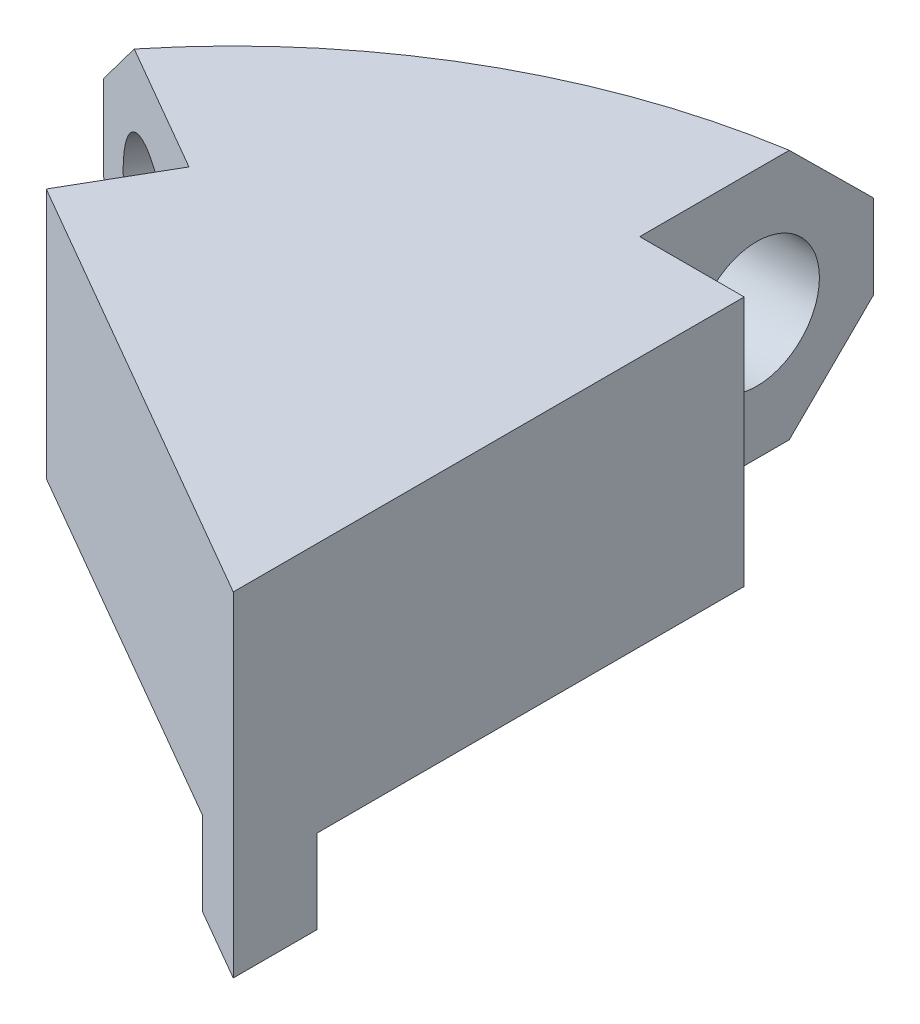
SolidWorks part; units mm, degrees
ref_plane "Alzado" through (0, 0, 0) normal (0, 0, 1) x (1, 0, 0)
ref_plane "Planta" through (0, 0, 0) normal (0, 1, 0) x (1, 0, 0)
ref_plane "Vista lateral" through (0, 0, 0) normal (1, 0, 0) x (0, 0, -1)
sketch "Croquis1" plane through (0, 0, 0) normal (0, 1, 0) x (1, 0, 0)
  line L6 (-136.7422, -20.0947) -> (-112.4935, -6.0947)
  line L7 (-112.4935, -6.0947) -> (-118.7435, 4.7306)
  line L8 (-118.7435, 4.7306) -> (-124.9935, 15.5559)
  line L9 (-124.9935, 15.5559) -> (-149.2422, 1.5559)
  line L10 (-149.2422, 69.033) -> (-124.9935, 55.033)
  line L11 (-124.9935, 55.033) -> (-118.7435, 65.8583)
  line L12 (-118.7435, 65.8583) -> (-112.4935, 76.6836)
  line L13 (-112.4935, 76.6836) -> (-136.7422, 90.6836)
  line L14 (-78.3054, 124.4222) -> (-78.3054, 96.4222)
  line L15 (-78.3054, 96.4222) -> (-65.8054, 96.4222)
  line L16 (-65.8054, 96.4222) -> (-53.3054, 96.4222)
  line L17 (-53.3054, 96.4222) -> (-53.3054, 124.4222)
  line L18 (5.1315, 90.6836) -> (-19.1172, 76.6836)
  line L19 (-19.1172, 76.6836) -> (-6.6172, 55.033)
  line L20 (-6.6172, 55.033) -> (17.6315, 69.033)
  line L21 (17.6315, 1.5559) -> (-6.6172, 15.5559)
  line L22 (-6.6172, 15.5559) -> (-12.8672, 4.7306)
  line L23 (-12.8672, 4.7306) -> (-19.1172, -6.0947)
  line L24 (-19.1172, -6.0947) -> (5.1315, -20.0947)
  line L25 (-78.3054, -53.8333) -> (-78.3054, -25.8333)
  line L26 (-78.3054, -25.8333) -> (-65.8054, -25.8333)
  line L27 (-65.8054, -25.8333) -> (-53.3054, -25.8333)
  line L28 (-53.3054, -25.8333) -> (-53.3054, -53.8333)
  arc A0 (-136.7422, -20.0947) -> (-78.3054, -53.8333) centre (-65.8054, 35.2945) ccw
  arc A1 (-53.3054, -53.8333) -> (5.1315, -20.0947) centre (-65.8054, 35.2945) ccw
  arc A2 (17.6315, 1.5559) -> (17.6315, 69.033) centre (-65.8054, 35.2945) ccw
  arc A3 (5.1315, 90.6836) -> (-53.3054, 124.4222) centre (-65.8054, 35.2945) ccw
  arc A4 (-149.2422, 69.033) -> (-149.2422, 1.5559) centre (-65.8054, 35.2945) ccw
  arc A5 (-78.3054, 124.4222) -> (-136.7422, 90.6836) centre (-65.8054, 35.2945) ccw
  dimension "D22" = 180
  dimension "D5" = 25
  dimension "D7" = 25
  dimension "D9" = 25
  dimension "D11" = 25
  dimension "D13" = 25
  dimension "D15" = 25
  dimension "D16" = 28
  dimension "D17" = 28
  dimension "D18" = 28
  dimension "D19" = 28
  dimension "D20" = 28
  dimension "D21" = 28
extrude "Saliente-Extruir1" add sketch "Croquis1" along normal mid plane 30
sketch "Croquis3" plane through (0, 15, 0) normal (0, 1, 0) x (1, 0, 0)
  line L0 (-65.8054, 96.4222) -> (-65.8054, 35.2945)
  line L1 (-53.3054, 96.4222) -> (-78.3054, 96.4222) construction
  line L3 (-118.7435, 65.8583) -> (-65.8054, 35.2945)
  line L4 (-112.4935, 76.6836) -> (-124.9935, 55.033) construction
  line L8 (-118.7435, 65.8583) -> (-112.4935, 76.6836)
  line L9 (-112.4935, 76.6836) -> (-136.7422, 90.6836)
  line L10 (-78.3054, 124.4222) -> (-78.3054, 96.4222)
  line L11 (-78.3054, 96.4222) -> (-65.8054, 96.4222)
  arc A1 (-136.7422, 90.6836) -> (-78.3054, 124.4222) centre (-65.8054, 35.2945) ccw
extrude "Cortar-Extruir2" cut sketch "Croquis3" against normal blind 30
sketch "Croquis4" plane through (-78.3054, 0, 0) normal (1, 0, 0) x (0, 0, -1)
  line L0 (110.4222, 15) -> (110.4222, -15) construction
  line L1 (96.4222, 15) -> (124.4222, 15) construction
  line L2 (96.4222, -15) -> (124.4222, -15) construction
  line L3 (96.4222, 0) -> (124.4222, 0) construction
  line L4 (96.4222, -15) -> (96.4222, 15) construction
  line L5 (124.4222, 15) -> (124.4222, -15) construction
  circle A0 centre (110.4222, 0) radius 7.5
  dimension "D1" = 15
extrude "Cortar-Extruir3" cut sketch "Croquis4" against normal blind 13
sketch "Croquis5" plane through (5.0816, 0, -8.8016) normal (-0.5, 0, 0.866) x (0.866, 0, 0.5)
  line L0 (-149.7641, 15) -> (-149.7641, -15) construction
  line L1 (-163.7641, 15) -> (-135.7641, 15) construction
  line L2 (-163.7641, -15) -> (-135.7641, -15) construction
  line L3 (-163.7641, 0) -> (-135.7641, 0) construction
  line L4 (-163.7641, 15) -> (-163.7641, -15) construction
  line L5 (-135.7641, 15) -> (-135.7641, -15) construction
  circle A0 centre (-149.7641, 0) radius 7.5
  dimension "D1" = 15
extrude "Cortar-Extruir4" cut sketch "Croquis5" against normal blind 13
sketch "Croquis6" plane through (0, -15, 0) normal (0, -1, 0) x (1, 0, 0)
  line L0 (-65.8054, -35.2945) -> (-74.4656, -40.2945)
  line L1 (-65.8054, -35.2945) -> (-118.7435, -65.8583) construction
  line L2 (-65.8054, -35.2945) -> (-65.8054, -45.2945)
  arc A0 (-74.4656, -40.2945) -> (-65.8054, -45.2945) centre (-65.8054, -35.2945) ccw
  dimension "D1" = 20
extrude "Saliente-Extruir2" add sketch "Croquis6" along normal blind 10 contours A0 L2 L0
chamfer "Chaflán1" distance 10 angle 45 1 edges at (-110.8054, -15, -113.2367)
chamfer "Chaflán2" distance 10 angle 45 1 edges at (-110.8054, 15, -113.2367)
